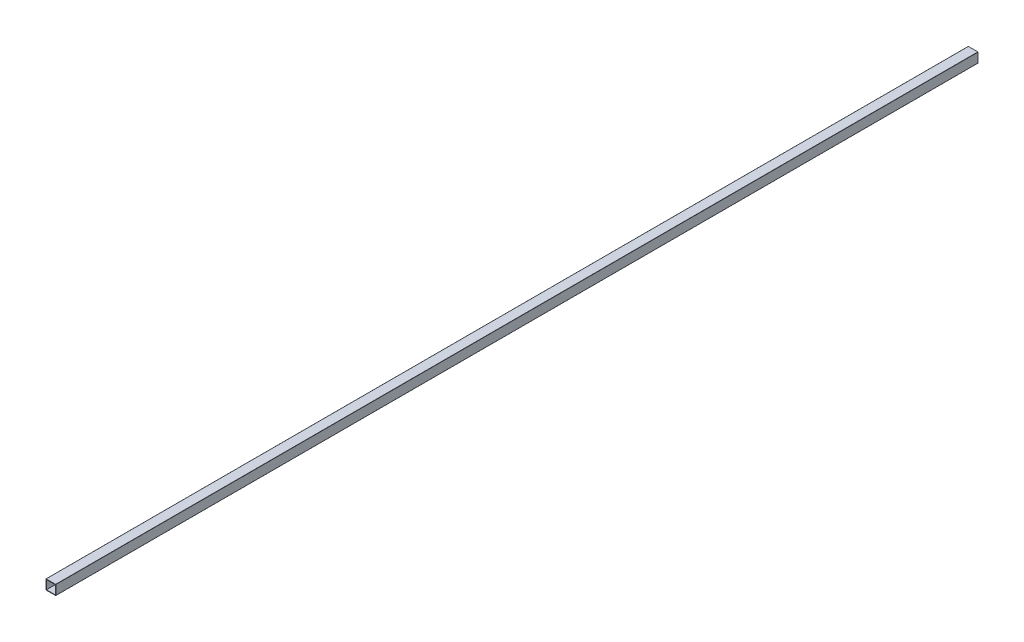
SolidWorks part; units mm, degrees
material "AISI 1035 Acero (SS)"
ref_plane "Alzado" through (0, 0, 0) normal (0, 0, 1) x (1, 0, 0)
ref_plane "Planta" through (0, 0, 0) normal (0, 1, 0) x (1, 0, 0)
ref_plane "Vista lateral" through (0, 0, 0) normal (1, 0, 0) x (0, 0, -1)
sketch "Croquis1" plane through (0, 0, 0) normal (0, 0, 1) x (1, 0, 0)
  line L0 (-28.71, -28.71) -> (-28.71, 28.71)
  line L1 (-30.75, -31.75) -> (30.75, -31.75)
  line L2 (-31.75, -30.75) -> (-31.75, 30.75)
  line L3 (-30.75, 31.75) -> (30.75, 31.75)
  line L4 (31.75, -30.75) -> (31.75, 30.75)
  line L5 (-31.75, -31.75) -> (31.75, 31.75) construction
  line L6 (-31.75, 31.75) -> (31.75, -31.75) construction
  line L7 (-28.71, 28.71) -> (28.71, 28.71)
  line L8 (28.71, -28.71) -> (28.71, 28.71)
  line L9 (-28.71, -28.71) -> (28.71, -28.71)
  line L10 (-31.75, 31.75) -> (31.75, 31.75) construction
  line L11 (31.75, -31.75) -> (31.75, 31.75) construction
  line L12 (-31.75, -31.75) -> (31.75, -31.75) construction
  line L13 (-31.75, -31.75) -> (-31.75, 31.75) construction
  arc A0 (30.75, 31.75) -> (31.75, 30.75) centre (30.75, 30.75) cw
  arc A1 (30.75, -31.75) -> (31.75, -30.75) centre (30.75, -30.75) ccw
  arc A2 (-30.75, -31.75) -> (-31.75, -30.75) centre (-30.75, -30.75) cw
  arc A3 (-31.75, 30.75) -> (-30.75, 31.75) centre (-30.75, 30.75) cw
  point P0 (0, 0)
  dimension "D2" = 1
  dimension "D1" = 63.5
  dimension "D3" = 3.04
extrude "Saliente-Extruir1" add sketch "Croquis1" along normal blind 6000
